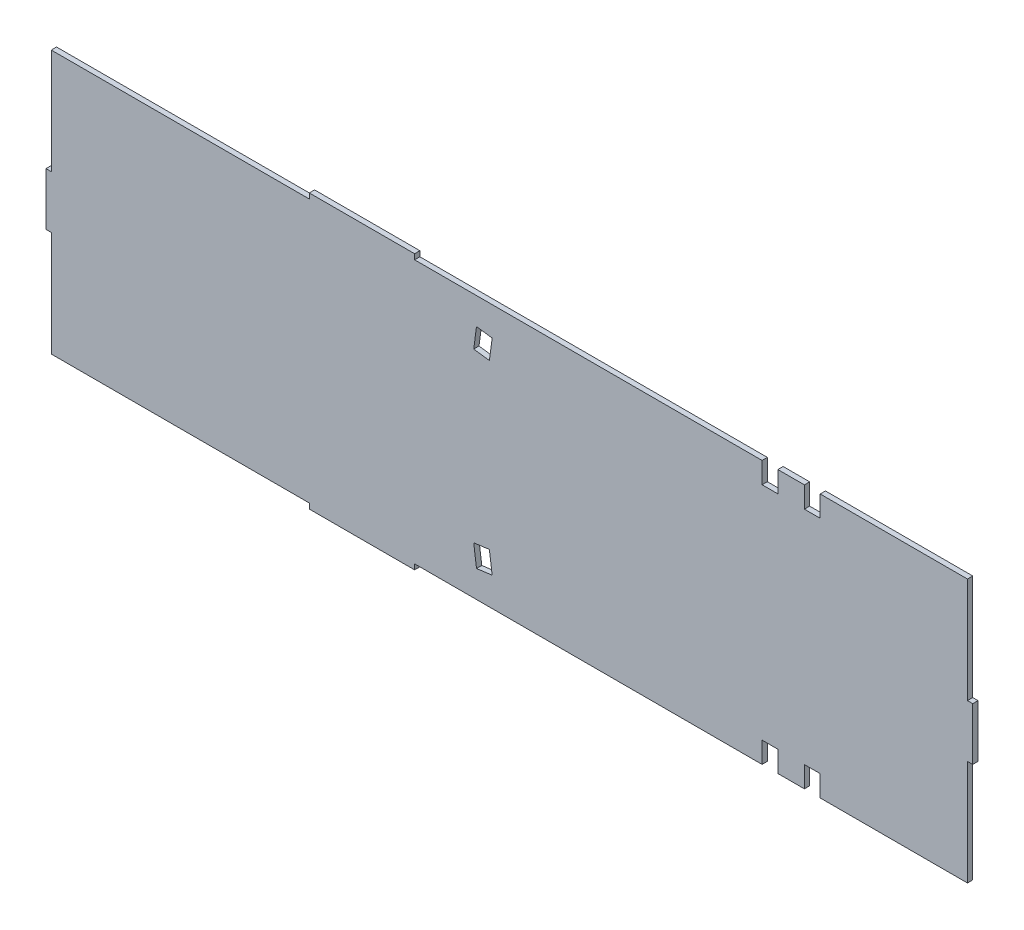
SolidWorks part; units mm, degrees
material "轻木"
ref_plane "前视基准面" through (0, 0, 0) normal (0, 0, 1) x (1, 0, 0)
ref_plane "上视基准面" through (0, 0, 0) normal (0, 1, 0) x (1, 0, 0)
ref_plane "右视基准面" through (0, 0, 0) normal (1, 0, 0) x (0, 0, -1)
sketch "草图1" plane through (0, 0, 0) normal (0, 0, 1) x (1, 0, 0)
  line L0 (0, 0) -> (0, 100)
  line L1 (0, 0) -> (350, 0)
  line L2 (0, 100) -> (350, 100)
  line L3 (350, 0) -> (350, 100)
  line L4 (100, 100) -> (100, 102)
  line L5 (100, 100) -> (140, 100)
  line L6 (100, 102) -> (140, 102)
  line L7 (140, 100) -> (140, 102)
  line L8 (350, 60) -> (352, 60)
  line L9 (350, 60) -> (350, 40)
  line L10 (352, 60) -> (352, 40)
  line L11 (350, 40) -> (352, 40)
  line L12 (100, 0) -> (100, -2)
  line L13 (100, 0) -> (140, 0)
  line L14 (100, -2) -> (140, -2)
  line L15 (140, 0) -> (140, -2)
  line L16 (0, 60) -> (2, 60)
  line L17 (0, 60) -> (0, 40)
  line L18 (2, 60) -> (2, 40)
  line L19 (0, 40) -> (2, 40)
  line L20 (2, 100) -> (2, 60)
  line L21 (2, 40) -> (2, 0)
extrude "凸台-拉伸1" add sketch "草图1" along normal blind 2 contours L0 L19 L18 L16 | L18 L21 L1 L3 L2 L20 | L2 L7 L6 L4 | L15 L1 L12 L14 | L3 L11 L10 L8
sketch3d "3D草图1"
  line L2 (171.381, 80.6723, 0) -> (171.6459, 82.6546, 0)
  line L3 (171.381, 80.6723, 0) -> (171.6459, 82.6546, 0)
  line L6 (171.6459, 82.6546, 0) -> (171.9108, 84.637, 0)
  line L7 (171.6459, 82.6546, 0) -> (171.9108, 84.637, 0)
  line L10 (171.9108, 84.637, 0) -> (172.1756, 86.6194, 0)
  line L11 (171.9108, 84.637, 0) -> (172.1756, 86.6194, 0)
  line L12 (172.1756, 86.6194, 0) -> (172.4405, 88.6018, 0)
  line L13 (172.1756, 86.6194, 0) -> (172.4405, 88.6018, 0)
sketch "草图2" plane through (0, 0, 0) normal (0, 0, -1) x (-1, 0, 0)
  line L0 (-168.4075, 81.0695) -> (-169.4669, 88.9991)
  line L1 (-169.4669, 88.9991) -> (-163.5197, 89.7937)
  line L2 (-163.5197, 89.7937) -> (-162.4603, 81.8641)
  line L3 (-162.4603, 81.8641) -> (-168.4075, 81.0695)
  line L7 (-162.4603, 18.1359) -> (-168.4075, 18.9305)
  line L8 (-163.5197, 10.2063) -> (-162.4603, 18.1359)
  line L9 (-169.4669, 11.0009) -> (-163.5197, 10.2063)
  line L10 (-168.4075, 18.9305) -> (-169.4669, 11.0009)
extrude "切除-拉伸1" cut sketch "草图2" against normal blind 10
sketch "草图3" plane through (0, 0, 2) normal (0, 0, 1) x (1, 0, 0)
  line L0 (285.061, 100) -> (297.061, 100)
  line L1 (288.061, 100) -> (294.061, 100)
  line L2 (297.061, 100) -> (297.061, 98)
  line L4 (297.061, 98) -> (297.061, 96)
  line L6 (297.061, 96) -> (297.061, 94)
  line L8 (297.061, 94) -> (297.061, 92)
  line L10 (297.061, 92) -> (285.061, 92)
  line L11 (294.061, 92) -> (288.061, 92)
  line L12 (285.061, 92) -> (285.061, 94)
  line L14 (285.061, 94) -> (285.061, 96)
  line L16 (285.061, 96) -> (285.061, 98)
  line L18 (285.061, 98) -> (285.061, 100)
  line L20 (288.061, 92) -> (288.061, 100)
  line L21 (294.061, 92) -> (294.061, 100)
  line L22 (0, 50) -> (352, 50)
  line L23 (0, 40) -> (0, 60) construction
  line L24 (352, 60) -> (352, 40) construction
  line L25 (294.061, 8) -> (294.061, 0)
  line L26 (288.061, 8) -> (288.061, 0)
  line L27 (294.061, 8) -> (288.061, 8)
  line L28 (288.061, 0) -> (294.061, 0)
  line M22 (350, 100) -> (140, 100)
extrude "切除-拉伸2" cut sketch "草图3" against normal blind 2 contours L11 L21 L20 M22 | L25 L28 L26 L27
sketch "草图4" plane through (0, 0, 2) normal (0, 0, 1) x (1, 0, 0)
  line L2 (271.9865, 92) -> (271.9865, 100)
  line L3 (140, 100) -> (288.061, 100) construction
  line L4 (271.9865, 98) -> (271.9865, 100) construction
  line L5 (271.9865, 100) -> (277.9865, 100)
  line L6 (277.9865, 98) -> (277.9865, 100) construction
  line L7 (277.9865, 100) -> (277.9865, 92)
  line L8 (271.9865, 92) -> (277.9865, 92)
  line L9 (0, 50) -> (352, 50)
  line L10 (0, 40) -> (0, 60) construction
  line L11 (352, 60) -> (352, 40) construction
  line L12 (271.9865, 8) -> (277.9865, 8)
  line L13 (277.9865, 0) -> (277.9865, 8)
  line L14 (271.9865, 0) -> (277.9865, 0)
  line L15 (271.9865, 8) -> (271.9865, 0)
  line M14 (288.061, 100) -> (140, 100)
  line M28 (140, 0) -> (288.061, 0)
extrude "切除-拉伸3" cut sketch "草图4" against normal blind 2 contours L12 L15 L13 M28 | L2 L8 L7 M14
